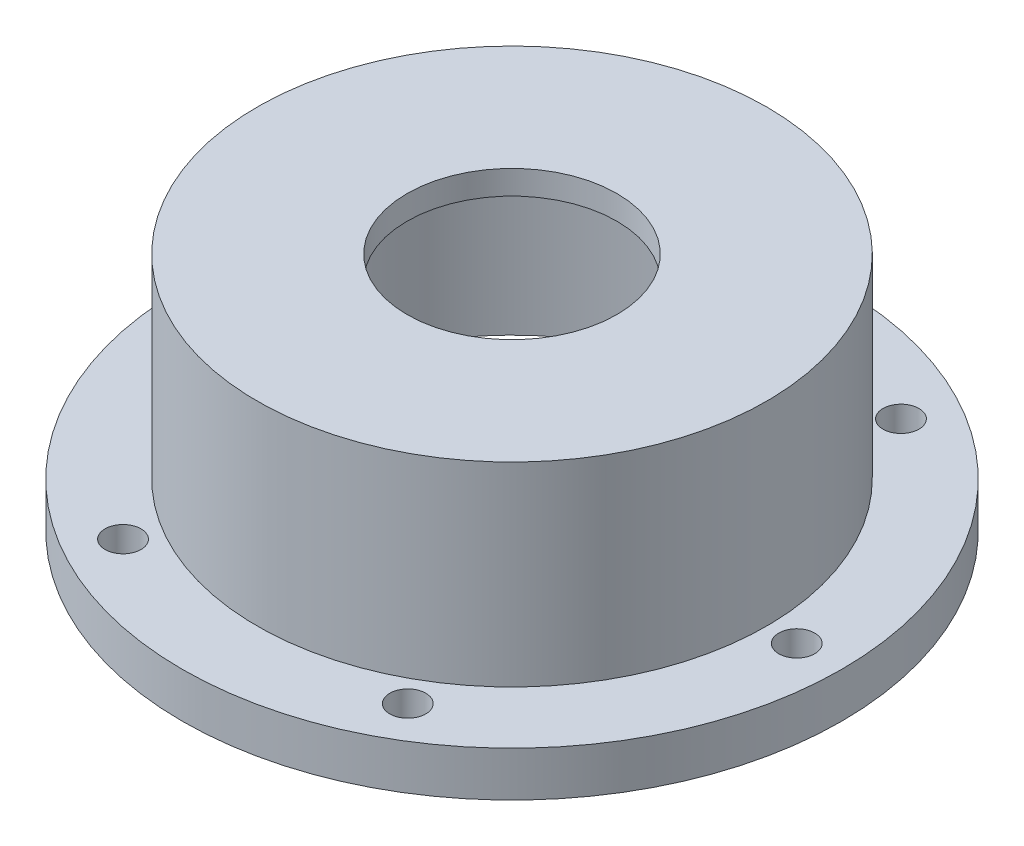
SolidWorks part; units mm, degrees
ref_plane "Front Plane" through (0, 0, 0) normal (0, 0, 1) x (1, 0, 0)
ref_plane "Top Plane" through (0, 0, 0) normal (0, 1, 0) x (1, 0, 0)
ref_plane "Right Plane" through (0, 0, 0) normal (1, 0, 0) x (0, 0, -1)
sketch "Sketch1" plane through (0, 0, 0) normal (0, 0, 1) x (1, 0, 0)
  line L0 (0, 0) -> (0, 216.512) construction
  line L1 (-80, 0) -> (-110, 0)
  line L2 (-110, 0) -> (-110, 15)
  line L3 (-110, 15) -> (-85, 15)
  line L4 (-85, 15) -> (-85, 80)
  line L5 (-85, 80) -> (85, 80)
  line L6 (85, 80) -> (85, 15)
  line L7 (85, 15) -> (110, 15)
  line L8 (110, 15) -> (110, 0)
  line L9 (110, 0) -> (80, 0)
  line L10 (80, 0) -> (80, 72)
  line L11 (80, 72) -> (-80, 72)
  line L12 (-80, 72) -> (-80, 0)
  dimension "D1" = 160
  dimension "D2" = 220
  dimension "D3" = 8
  dimension "D4" = 5
  dimension "D5" = 5
  dimension "D6" = 65
  dimension "D7" = 15
revolve "Revolve1" add sketch "Sketch1" angle 360 about L0
sketch "Sketch2" plane through (0, 80, 0) normal (0, 1, 0) x (1, 0, 0)
  circle A0 centre (0, 0) radius 35
  dimension "D1" = 70
extrude "Cut-Extrude1" cut sketch "Sketch2" against normal up to surface (8 mm away) up to face at (0, 72, -80)
hole_wizard "Ø12.0 (12) Diameter Hole1" positions "Sketch5" profile "Sketch6" hole size "Ø12.0" standard "ANSI Metric" end condition through all
sketch "Sketch5" plane through (0, 15, 0) normal (0, 1, 0) x (1, 0, 0)
  circle A0 centre (0, 0) radius 95 construction
  point P5 (-95, 0)
  point P15 (-47.5, 82.2724)
  point P16 (47.5, 82.2724)
  point P17 (95, 0)
  point P18 (47.5, -82.2724)
  point P19 (-47.5, -82.2724)
  dimension "D1" = 190
  dimension "D2" = 6
sketch "Sketch6" plane through (-47.5, 15, 82.2724) normal (1, 0, 0) x (0, 0, 1)
  line L0 (0, 0) -> (0, 15)
  line L1 (0, 15) -> (6, 15)
  line L2 (6, 15) -> (6, 0)
  line L5 (6, 0) -> (0, 0)
  line L11 (0, -6.35) -> (0, 107.95) construction
  dimension "Thru Hole Dia." = 12
  dimension "Thru Hole Depth" = 15
sketch "Sketch7" plane through (0, 72, 0) normal (0, -1, 0) x (1, 0, 0)
  circle A0 centre (0, 0) radius 58.5 construction
  circle A1 centre (0, 58.5) radius 10
  circle A2 centre (58.5, 0) radius 10
  circle A3 centre (0, -58.5) radius 10
  circle A4 centre (-58.5, 0) radius 10
  point P14 (0, 0)
  dimension "D1" = 117
  dimension "D2" = 20
  dimension "D3" = 4
extrude "Cut-Extrude2" cut sketch "Sketch7" against normal blind 3
